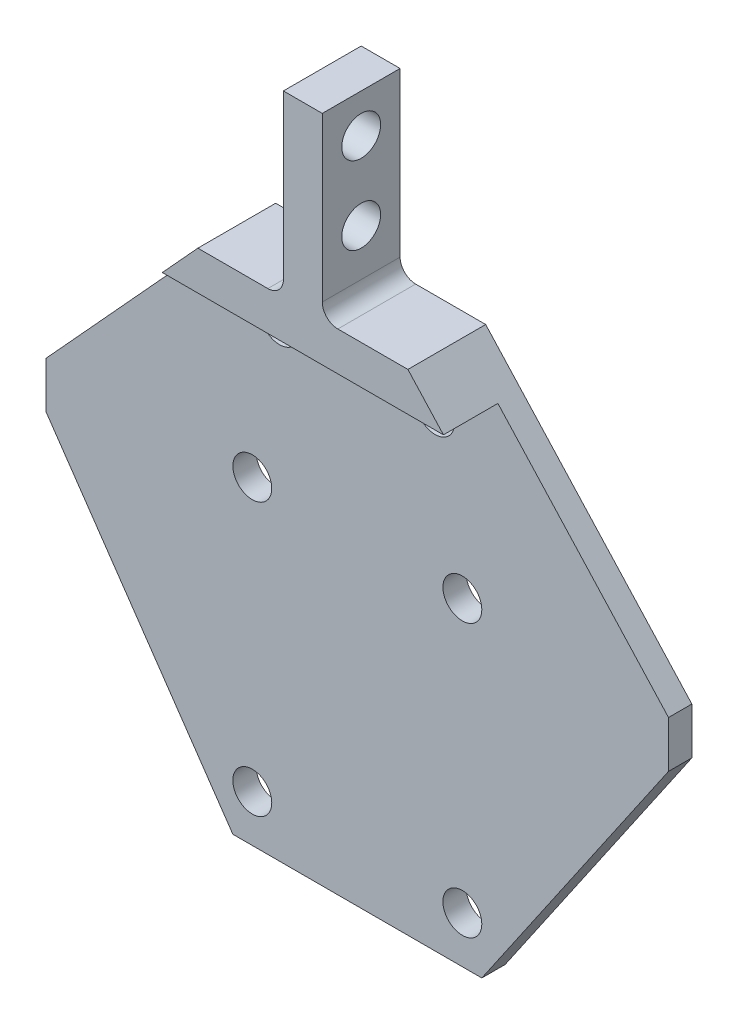
SolidWorks part; units mm, degrees
ref_plane "Front Plane" through (0, 0, 0) normal (0, 0, 1) x (1, 0, 0)
ref_plane "Top Plane" through (0, 0, 0) normal (0, 1, 0) x (1, 0, 0)
ref_plane "Right Plane" through (0, 0, 0) normal (1, 0, 0) x (0, 0, -1)
sketch "Sketch2" plane through (0, 0, 0) normal (0, 0, 1) x (1, 0, 0)
  line L0 (-13.5, 0) -> (0, 0)
  line L1 (0, 0) -> (13.5, 0)
  line L2 (0, 0) -> (0, -35) construction
  line L3 (-13.5, -35) -> (13.5, -35) construction
  line L4 (0, -17.5) -> (18.3872, -17.5) construction
  line L5 (16, -41) -> (40, -6)
  line L6 (-16, -41) -> (16, -41)
  line L7 (-40, -6) -> (-40, 0)
  line L8 (-13.5, 29) -> (13.5, 29)
  line L9 (40, -6) -> (40, 0)
  line L10 (-25, -27.875) -> (25.2743, 16.115) construction
  line L11 (-25.2743, 16.115) -> (25, -27.875) construction
  line L12 (-40, -6) -> (-16, -41)
  line L13 (-13.5, 0) -> (-40, 0) construction
  line L14 (-40, 0) -> (-13.5, 29)
  line L15 (-13.5, 29) -> (13.5, 29)
  line L16 (13.5, 29) -> (40, 0)
  circle A0 centre (-13.5, 0) radius 2.5
  circle A1 centre (13.5, 0) radius 2.5
  circle A2 centre (13.5, -35) radius 2.5
  circle A3 centre (-13.5, -35) radius 2.5
  point P13 (0, -6)
  dimension "D3" = 5
  dimension "D4" = 5
  dimension "D6" = 6
  dimension "D1" = 13.5
  dimension "D2" = 13.5
  dimension "D5" = 35
extrude "Boss-Extrude1" add sketch "Sketch2" along normal blind 3
sketch "Sketch3" plane through (0, 0, 3) normal (0, 0, 1) x (1, 0, 0)
  line L0 (0, 0) -> (0, 46) construction
  line L1 (-13.5, 29) -> (13.5, 29) construction
  circle A0 centre (0, 23) radius 2.5
  dimension "D1" = 5
  dimension "D2" = 6
sketch "Sketch4" plane through (0, 0, 3) normal (0, 0, 1) x (1, 0, 0)
  line L0 (-13.5, 29) -> (-18.069, 24)
  line L1 (-40, 0) -> (-13.5, 29) construction
  line L2 (-18.069, 24) -> (18.069, 24)
  line L3 (13.5, 29) -> (40, 0) construction
  line L4 (18.069, 24) -> (13.5, 29)
  line L5 (-13.5, 29) -> (13.5, 29) construction
  line L6 (13.5, 29) -> (-13.5, 29)
  dimension "D1" = 5
extrude "Boss-Extrude2" add sketch "Sketch4" along normal blind 7
ref_plane "Plane1" through (-0.3044, -56.1681, -48.6762) normal (1, 0, 0) x (0, 0, -1)
sketch "Sketch6" plane through (-0.3044, -56.1681, -48.6762) normal (1, 0, 0) x (0, 0, -1)
  line L0 (-53.6762, 85.1681) -> (-53.6762, 125.1681) construction
  line L1 (-58.6762, 85.1681) -> (-48.6762, 85.1681) construction
  dimension "D1" = 40
sketch "Sketch7" plane through (-0.3044, -56.1681, -48.6762) normal (1, 0, 0) x (0, 0, -1)
  line L0 (-58.6762, 85.1681) -> (-48.6762, 85.1681) construction
  line L1 (-48.6762, 85.1681) -> (-58.6762, 85.1681)
  line L2 (-48.6762, 85.1681) -> (-48.6762, 108.1681)
  line L3 (-48.6762, 108.1681) -> (-58.6762, 108.1681)
  line L4 (-58.6762, 85.1681) -> (-58.6762, 108.1681)
  line L5 (-53.6762, 85.1681) -> (-53.6762, 125.1681) construction
  circle A2 centre (-53.6762, 103.1681) radius 2.5
  circle A3 centre (-53.6762, 93.1681) radius 2.5
  dimension "D4" = 8
  dimension "D5" = 10
  dimension "D6" = 5
  dimension "D7" = 5
  dimension "D3" = 5
  dimension "D1" = 5
  dimension "D2" = 5
ref_plane "Plane2" through (-0.3044, -56.1681, -48.6762) normal (1, 0, 0) x (0, 0, -1)
extrude "Boss-Extrude4" add sketch "Sketch7" along normal blind 2.8 and the other way blind 2.2
sketch "Sketch9" plane through (0, 0, 3) normal (0, 0, 1) x (1, 0, 0)
  line L0 (0, 0) -> (0, 46) construction
  line L1 (-18.069, 24) -> (18.069, 24) construction
  line L2 (0, 0) -> (0, 30.0099) construction
  circle A0 centre (-10, 19) radius 2.5
  circle A1 centre (10, 19) radius 2.5
  dimension "D3" = 5
  dimension "D1" = 10
  dimension "D2" = 5
extrude "Cut-Extrude1" cut sketch "Sketch9" against normal blind 10
fillet "Fillet5" radius 2 2 edges at (2.4956, 29, 5) (-2.5044, 29, 5)
